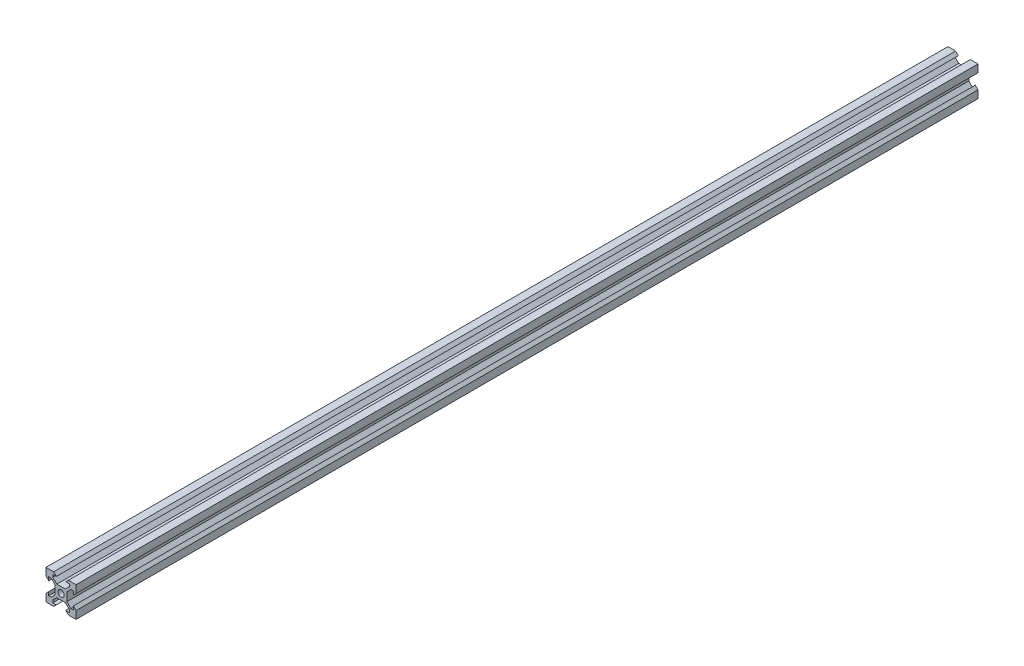
SolidWorks part; units mm, degrees
ref_plane "Plan de face" through (0, 0, 0) normal (0, 0, 1) x (1, 0, 0)
ref_plane "Plan de dessus" through (0, 0, 0) normal (0, 1, 0) x (1, 0, 0)
ref_plane "Plan de droite" through (0, 0, 0) normal (1, 0, 0) x (0, 0, -1)
sketch "Esquisse1" plane through (0, 0, 0) normal (0, 0, 1) x (1, 0, 0)
  line L45 (-5.6277, 8.2661) -> (14.3723, 8.2661)
  line L46 (-5.6277, 8.2661) -> (-5.6277, -11.7339)
  line L47 (-5.6277, -11.7339) -> (14.3723, -11.7339)
  line L48 (14.3723, 8.2661) -> (14.3723, -11.7339)
  dimension "D1" = 20
  dimension "D2" = 20
extrude "Boss.-Extru.1" add sketch "Esquisse1" along normal blind 600
sketch "Esquisse2" plane through (0, 0, 0) normal (0, 0, -1) x (-1, 0, 0)
  line L0 (-14.3723, -11.7339) -> (-14.3723, 8.2661) construction
  line L1 (5.6277, -11.7339) -> (-14.3723, -11.7339) construction
  line L2 (-9.2723, 8.2661) -> (0.5277, 8.2661)
  line L3 (-14.3723, 8.2661) -> (5.6277, 8.2661) construction
  line L4 (0.5277, 8.2661) -> (-1.2723, 6.4661)
  line L5 (-1.2723, 6.4661) -> (1.1277, 6.4661)
  line L6 (1.1277, 6.4661) -> (1.1277, 4.8261)
  line L7 (1.1277, 4.8261) -> (-1.5323, 2.1661)
  line L8 (-1.5323, 2.1661) -> (-7.2123, 2.1661)
  line L9 (-7.2123, 2.1661) -> (-9.8723, 4.8261)
  line L10 (-9.8723, 4.8261) -> (-9.8723, 6.4661)
  line L11 (-9.8723, 6.4661) -> (-7.4723, 6.4661)
  line L12 (-7.4723, 6.4661) -> (-9.2723, 8.2661)
  line L13 (2.1877, -7.2339) -> (-0.4723, -4.5739)
  line L14 (-0.4723, -4.5739) -> (-0.4723, 1.1061)
  line L15 (-0.4723, 1.1061) -> (2.1877, 3.7661)
  line L16 (2.1877, 3.7661) -> (3.8277, 3.7661)
  line L17 (3.8277, 3.7661) -> (3.8277, 1.3661)
  line L18 (3.8277, 1.3661) -> (5.6277, 3.1661)
  line L19 (5.6277, 3.1661) -> (5.6277, -6.6339)
  line L20 (5.6277, -6.6339) -> (3.8277, -4.8339)
  line L21 (3.8277, -4.8339) -> (3.8277, -7.2339)
  line L22 (3.8277, -7.2339) -> (2.1877, -7.2339)
  line L23 (-9.8723, -8.2939) -> (-7.2123, -5.6339)
  line L24 (-7.2123, -5.6339) -> (-1.5323, -5.6339)
  line L25 (-1.5323, -5.6339) -> (1.1277, -8.2939)
  line L26 (1.1277, -8.2939) -> (1.1277, -9.9339)
  line L27 (1.1277, -9.9339) -> (-1.2723, -9.9339)
  line L28 (-1.2723, -9.9339) -> (0.5277, -11.7339)
  line L29 (0.5277, -11.7339) -> (-9.2723, -11.7339)
  line L30 (-9.2723, -11.7339) -> (-7.4723, -9.9339)
  line L31 (-7.4723, -9.9339) -> (-9.8723, -9.9339)
  line L32 (-9.8723, -9.9339) -> (-9.8723, -8.2939)
  line L33 (-10.9323, 3.7661) -> (-8.2723, 1.1061)
  line L34 (-8.2723, 1.1061) -> (-8.2723, -4.5739)
  line L35 (-8.2723, -4.5739) -> (-10.9323, -7.2339)
  line L36 (-10.9323, -7.2339) -> (-12.5723, -7.2339)
  line L37 (-12.5723, -7.2339) -> (-12.5723, -4.8339)
  line L38 (-12.5723, -4.8339) -> (-14.3723, -6.6339)
  line L39 (-14.3723, -6.6339) -> (-14.3723, 3.1661)
  line L40 (-14.3723, 3.1661) -> (-12.5723, 1.3661)
  line L41 (-12.5723, 1.3661) -> (-12.5723, 3.7661)
  line L42 (-12.5723, 3.7661) -> (-10.9323, 3.7661)
  circle A0 centre (-4.3723, -1.7339) radius 2.1
  point P5 (-14.3723, -1.7339)
  point P9 (-4.3723, -11.7339)
  point P17 (-4.3723, 2.1661)
  point P54 (-4.3723, -1.7339)
  dimension "D1" = 4.2
  dimension "D2" = 135
  dimension "D3" = 1.64
  dimension "D4" = 5.68
  dimension "D5" = 1.8
  dimension "D6" = 6.2
  dimension "D7" = 11
  dimension "D8" = 4
extrude "Enlèv. mat.-Extru.1" cut sketch "Esquisse2" against normal up to next
